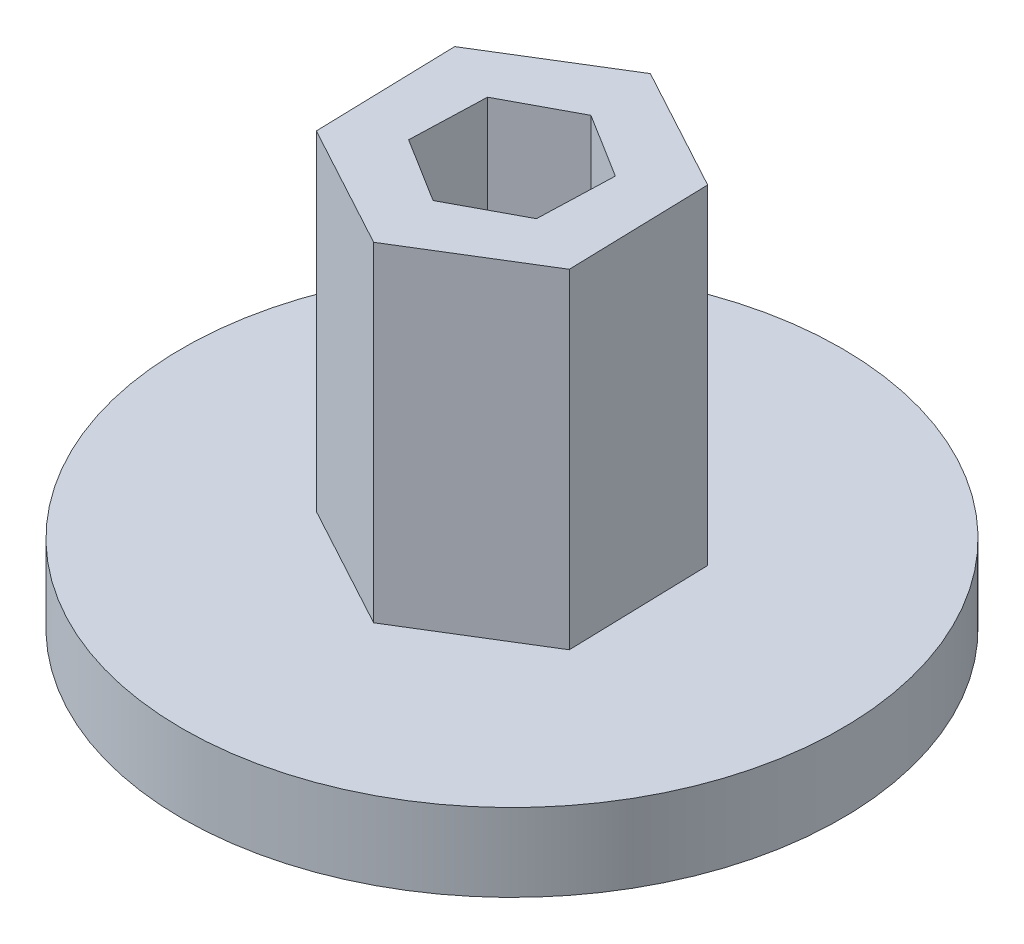
SolidWorks part; units mm, degrees
ref_plane "Front" through (0, 0, 0) normal (0, 0, 1) x (1, 0, 0)
ref_plane "Top" through (0, 0, 0) normal (0, 1, 0) x (1, 0, 0)
ref_plane "Right" through (0, 0, 0) normal (1, 0, 0) x (0, 0, -1)
sketch "Sketch1" plane through (0, 0, 0) normal (0, 1, 0) x (1, 0, 0)
  circle A0 centre (0, 0) radius 12.7
  dimension "D1" = 25.4
extrude "Boss-Extrude1" add sketch "Sketch1" along normal blind 3
sketch "Sketch2" plane through (0, 3, 0) normal (0, 1, 0) x (1, 0, 0)
  line L1 (0.1489, -5.48) -> (4.8203, -2.6111)
  line L2 (4.8203, -2.6111) -> (4.6714, 2.8689)
  line L3 (4.6714, 2.8689) -> (-0.1489, 5.48)
  line L4 (-0.1489, 5.48) -> (-4.8203, 2.6111)
  line L5 (-4.8203, 2.6111) -> (-4.6714, -2.8689)
  line L6 (-4.6714, -2.8689) -> (0.1489, -5.48)
  circle A0 centre (0, 0) radius 4.7476 construction
  dimension "D1" = 5.48
extrude "Boss-Extrude2" add sketch "Sketch2" along normal blind 12.7
sketch "Sketch6" plane through (0, 15.7, 0) normal (0, 1, 0) x (1, 0, 0)
  line L1 (-2.5979, -1.386) -> (-0.0986, -2.9428)
  line L2 (-0.0986, -2.9428) -> (2.4993, -1.5568)
  line L3 (2.4993, -1.5568) -> (2.5979, 1.386)
  line L4 (2.5979, 1.386) -> (0.0986, 2.9428)
  line L5 (0.0986, 2.9428) -> (-2.4993, 1.5568)
  line L6 (-2.4993, 1.5568) -> (-2.5979, -1.386)
  circle A1 centre (0, 0) radius 2.55 construction
  dimension "D1" = 5.1
extrude "Cut-Extrude1" cut sketch "Sketch6" against normal blind 23
